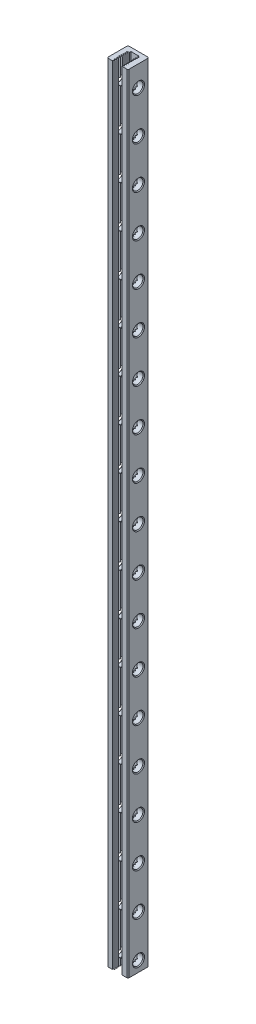
SolidWorks part; units mm, degrees
ref_plane "Front Plane" through (0, 0, 0) normal (0, 0, 1) x (1, 0, 0)
ref_plane "Top Plane" through (0, 0, 0) normal (0, 1, 0) x (1, 0, 0)
ref_plane "Right Plane" through (0, 0, 0) normal (1, 0, 0) x (0, 0, -1)
sketch "Sketch1" plane through (0, 0, 0) normal (0, 1, 0) x (1, 0, 0)
  line L1 (0, 0) -> (8, 0)
  line L2 (0, 0) -> (0, 8)
  line L3 (0, 8) -> (8, 8)
  line L4 (8, 0) -> (8, 8)
  dimension "D1" = 8
  dimension "D2" = 8
extrude "Boss-Extrude1" add sketch "Sketch1" along normal blind 300
sketch "Sketch2" plane through (0, 0, 0) normal (0, -1, 0) x (1, 0, 0)
  line L0 (5.652, 0) -> (2.0084, 0)
  line L1 (2.0084, 0) -> (2.0084, -0.2082)
  line L2 (2.0084, -0.2082) -> (2.54, -0.5151)
  line L3 (2.54, -0.5151) -> (1.6737, -0.8651)
  line L4 (1.6737, -0.8651) -> (2.54, -1.2151)
  line L5 (2.54, -1.2151) -> (1.6737, -1.5727)
  line L6 (1.6737, -1.5727) -> (2.54, -1.9151)
  line L7 (2.54, -1.9151) -> (1.6737, -2.2651)
  line L8 (1.6737, -2.2651) -> (2.54, -2.6151)
  line L9 (2.54, -2.6151) -> (1.6737, -2.9651)
  line L10 (1.6737, -2.9651) -> (2.54, -3.3151)
  line L11 (2.54, -3.3151) -> (1.6737, -3.6651)
  line L12 (1.6737, -3.6651) -> (2.54, -4.0151)
  line L13 (2.54, -4.0151) -> (1.6737, -4.3651)
  line L14 (1.6737, -4.3651) -> (2.54, -4.7151)
  line L15 (2.54, -4.7151) -> (1.6737, -5.0651)
  line L16 (1.6737, -5.0651) -> (2.54, -5.4151)
  line L17 (2.54, -5.4151) -> (1.6737, -5.7651)
  line L18 (1.6737, -5.7651) -> (2.54, -6.0264)
  line L19 (2.54, -6.0264) -> (2.54, -6.6)
  line L20 (2.54, -6.6) -> (5.46, -6.6)
  line L21 (5.46, -6.6) -> (5.46, -6.4988)
  line L22 (5.46, -6.4988) -> (6.1067, -6.2375)
  line L23 (6.1067, -6.2375) -> (5.46, -5.8875)
  line L24 (5.46, -5.8875) -> (6.1067, -5.5375)
  line L25 (6.1067, -5.5375) -> (5.46, -5.1875)
  line L26 (5.46, -5.1875) -> (6.1067, -4.8375)
  line L27 (6.1067, -4.8375) -> (5.46, -4.4875)
  line L28 (5.46, -4.4875) -> (6.1067, -4.1375)
  line L29 (6.1067, -4.1375) -> (5.46, -3.7875)
  line L30 (5.46, -3.7875) -> (6.1067, -3.4375)
  line L31 (6.1067, -3.4375) -> (5.46, -3.0875)
  line L32 (5.46, -3.0875) -> (6.1067, -2.7375)
  line L33 (6.1067, -2.7375) -> (5.46, -2.3875)
  line L34 (5.46, -2.3875) -> (6.1067, -2.0375)
  line L35 (6.1067, -2.0375) -> (5.46, -1.6875)
  line L36 (5.46, -1.6875) -> (6.1067, -1.3451)
  line L37 (6.1067, -1.3451) -> (5.46, -0.9875)
  line L38 (5.46, -0.9875) -> (6.1067, -0.6375)
  line L39 (6.1067, -0.6375) -> (5.652, -0.375)
  line L40 (5.652, -0.375) -> (5.652, 0)
  line L41 (0, -8) -> (0, 0) construction
  line L42 (8, -8) -> (0, -8) construction
  line L43 (0, 0) -> (8, 0) construction
  point P41 (0, 0)
  point P42 (0, 0)
  point P43 (0, 0)
  point P44 (0, 0)
  point P51 (0, 0)
  point P52 (0, 0)
  point P53 (4, -6.6)
  dimension "D1" = 2.92
  dimension "D2" = 0.8663
  dimension "D3" = 6.6
  dimension "D4" = 0.6467
  dimension "D5" = 4.433
  dimension "D6" = 4
extrude "Cut-Extrude1" cut sketch "Sketch2" against normal through all contours L0 L1 L2 L3 L4 L5 L6 L7 L8 L9 L10 L11 L12 L13 L14 L15 L16 L17 L18 L19 L20 L21 L22 L23 L24 L25 L26 L27 L28 L29 L30 L31 L32 L33 L34 L35 L36 L37 L38 L39 L40
sketch "Sketch3" plane through (8, 0, 0) normal (1, 0, 0) x (0, 0, -1)
  line L0 (0, 0) -> (8, 0) construction
  line L1 (8, 300) -> (8, 0) construction
  circle A0 centre (4, 4) radius 2
  dimension "D1" = 4
  dimension "D2" = 4
  dimension "D3" = 4
extrude "Cut-Extrude2" cut sketch "Sketch3" against normal through all
chamfer "Chamfer1" distance 0.3 angle 45 2 edges at (0, 4, -6) (8, 4, -6)
chamfer "Chamfer2" distance 0.3 angle 45 4 edges at (0, 150, -8) (0, 150, 0) (8, 150, -8) (8, 150, 0)
pattern_linear "LPattern1" count 19 spacing 16 along (0, 1, 0) of "Cut-Extrude2", "Chamfer1"
